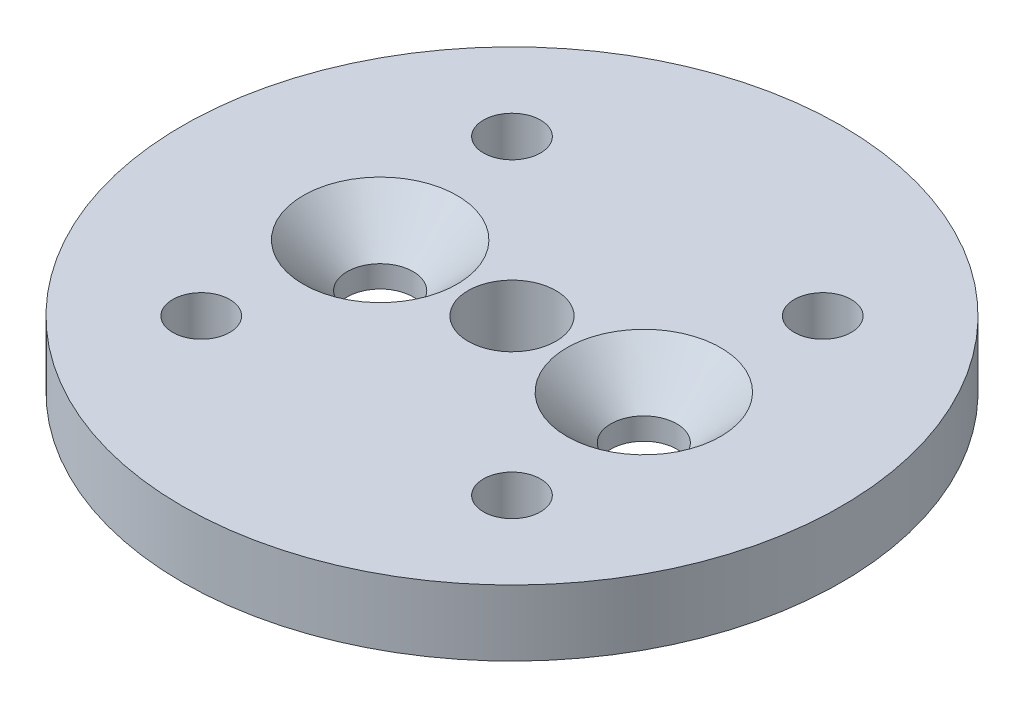
SolidWorks part; units mm, degrees
material "6061-T4 (SS)"
ref_plane "Front Plane" through (0, 0, 0) normal (0, 0, 1) x (1, 0, 0)
ref_plane "Top Plane" through (0, 0, 0) normal (0, 1, 0) x (1, 0, 0)
ref_plane "Right Plane" through (0, 0, 0) normal (1, 0, 0) x (0, 0, -1)
sketch "Sketch1" plane through (0, 0, 0) normal (0, 1, 0) x (1, 0, 0)
  circle A0 centre (0, 0) radius 15
  circle A1 centre (0, 0) radius 2
  dimension "D1" = 30
  dimension "D2" = 4
extrude "Boss-Extrude1" add sketch "Sketch1" along normal blind 3
sketch "Sketch2" plane through (0, 3, 0) normal (0, 1, 0) x (1, 0, 0)
  circle A0 centre (6, 0) radius 1.5
  circle A1 centre (-6, 0) radius 1.5
  circle A2 centre (0, 0) radius 2 construction
  dimension "D1" = 3
  dimension "D2" = 3
  dimension "D3" = 6
  dimension "D4" = 6
extrude "Cut-Extrude1" cut sketch "Sketch2" against normal blind 3
chamfer "Chamfer1" distance 2 angle 45 2 edges at (6, 3, 1.5) (-6, 3, 1.5)
sketch "Sketch3" plane through (0, 3, 0) normal (0, 1, 0) x (1, 0, 0)
  circle A0 centre (-7.0721, 7.0721) radius 1.3
  circle A1 centre (7.0721, 7.0721) radius 1.3
  circle A2 centre (7.0721, -7.0721) radius 1.3
  circle A3 centre (-7.0721, -7.0721) radius 1.3
  point P0 (0, 0)
  dimension "D1" = 14.1443
  dimension "D2" = 14.1443
  dimension "D3" = 2.6
  dimension "D4" = 2.6
  dimension "D5" = 2.6
  dimension "D6" = 2.6
extrude "Cut-Extrude2" cut sketch "Sketch3" against normal blind 3
